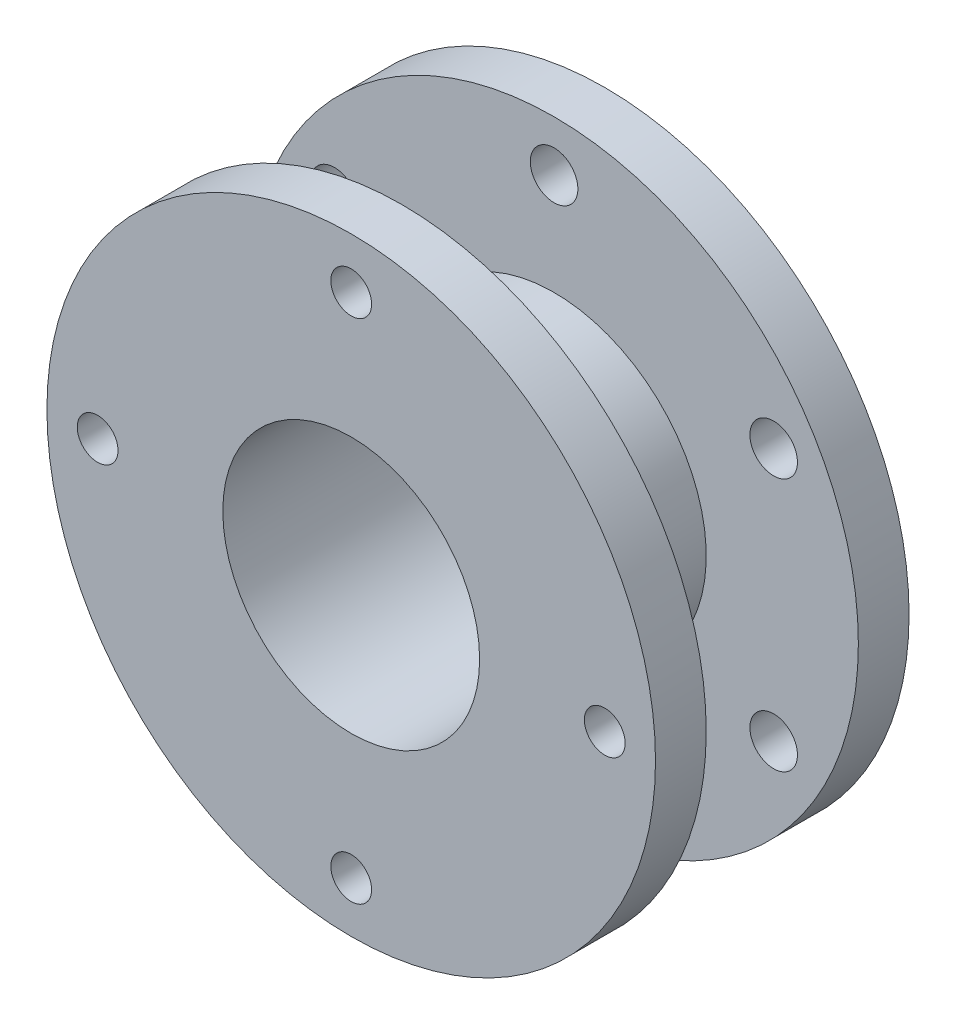
SolidWorks part; units mm, degrees
ref_plane "Front Plane" through (0, 0, 0) normal (0, 0, 1) x (1, 0, 0)
ref_plane "Top Plane" through (0, 0, 0) normal (0, 1, 0) x (1, 0, 0)
ref_plane "Right Plane" through (0, 0, 0) normal (1, 0, 0) x (0, 0, -1)
sketch "Sketch1" plane through (0, 0, 0) normal (0, 0, 1) x (1, 0, 0)
  circle A0 centre (0, 0) radius 38.1
  dimension "D1" = 76.2
extrude "Boss-Extrude1" add sketch "Sketch1" along normal blind 6.35
sketch "Sketch2" plane through (0, 0, 6.35) normal (0, 0, 1) x (1, 0, 0)
  circle A0 centre (0, 0) radius 19.05
  dimension "D1" = 38.1
extrude "Boss-Extrude2" add sketch "Sketch2" along normal blind 19.05 contours A0
sketch "Sketch3" plane through (0, 0, 25.4) normal (0, 0, 1) x (1, 0, 0)
  circle A0 centre (0, 0) radius 16.0782
  dimension "D1" = 32.1564
extrude "Cut-Extrude1" cut sketch "Sketch3" against normal through all
sketch "Sketch4" plane through (0, 0, 0) normal (0, 0, 1) x (1, 0, 0)
  line L0 (0, 0) -> (0, 31.75) construction
  circle A0 centre (0, 0) radius 31.75 construction
  circle A1 centre (0, 31.75) radius 2.9787
  circle A2 centre (27.4963, 15.875) radius 2.9787
  circle A3 centre (27.4963, -15.875) radius 2.9787
  circle A4 centre (0, -31.75) radius 2.9787
  circle A5 centre (-27.4963, -15.875) radius 2.9787
  circle A6 centre (-27.4963, 15.875) radius 2.9787
  point P17 (0, 0)
  dimension "D2" = 63.5
  dimension "D1" = 6
extrude "Cut-Extrude2" cut sketch "Sketch4" along normal up to next
sketch "Sketch5" plane through (0, 0, 0) normal (0, 0, -1) x (-1, 0, 0)
  circle A0 centre (0, 0) radius 21.7297
  circle A1 centre (0, 0) radius 23.8633
  dimension "D1" = 2.1336
  dimension "D2" = 47.7266
extrude "Cut-Extrude3" cut sketch "Sketch5" against normal blind 1.3208
fillet "Fillet1" radius 0.127 2 edges at (-21.7297, 0, 0) (-23.8633, 0, 0)
fillet "Fillet2" radius 0.254 2 edges at (-21.7297, 0, 1.3208) (-23.8633, 0, 1.3208)
ref_plane "Plane1" through (0, 0, 6.35) normal (0, 0, 1) x (1, 0, 0)
ref_plane "Plane2" through (0, 0, 15.875) normal (0, 0, 1) x (1, 0, 0)
mirror "Mirror1" about plane through (0, 0, 15.875) normal (0, 0, 1) of "Boss-Extrude1"
sketch "Sketch6" plane through (0, 0, 25.4) normal (0, 0, -1) x (-1, 0, 0)
  circle A0 centre (0, 0) radius 16.0782
  circle A1 centre (0, 0) radius 16.0782 construction
extrude "Cut-Extrude4" cut sketch "Sketch6" against normal through all
sketch "Sketch7" plane through (0, 0, 31.75) normal (0, 0, 1) x (1, 0, 0)
  line L0 (0, 0) -> (0, 31.75) construction
  line L1 (0, 0) -> (31.75, 0) construction
  line L2 (0, 0) -> (0, -31.75) construction
  line L3 (0, 0) -> (-31.75, 0) construction
  circle A0 centre (0, 0) radius 31.75 construction
  circle A2 centre (0, 0) radius 38.1 construction
  point P10 (0, 0)
  dimension "D2" = 6.35
  dimension "D1" = 4
hole_wizard "Tap Drill for 1/4-20 Tap1" positions "3DSketch1" profile "Sketch9" hole size "1/4-20" standard "ANSI Inch"
sketch3d "3DSketch1"
  point P0 (0, 31.75, 31.75)
  point P3 (31.75, 0, 31.75)
  point P6 (0, -31.75, 31.75)
  point P9 (-31.75, 0, 31.75)
sketch "Sketch9" plane through (0, 31.75, 31.75) normal (1, 0, 0) x (0, -1, 0)
  line L0 (0, 0) -> (0, 6.35)
  line L1 (0, 6.35) -> (2.5527, 6.35)
  line L2 (2.5527, 6.35) -> (2.5527, 0)
  line L5 (2.5527, 0) -> (0, 0)
  line L11 (0, -6.35) -> (0, 107.95) construction
  dimension "Thru Hole Dia." = 5.1054
  dimension "Thru Hole Depth" = 6.35
